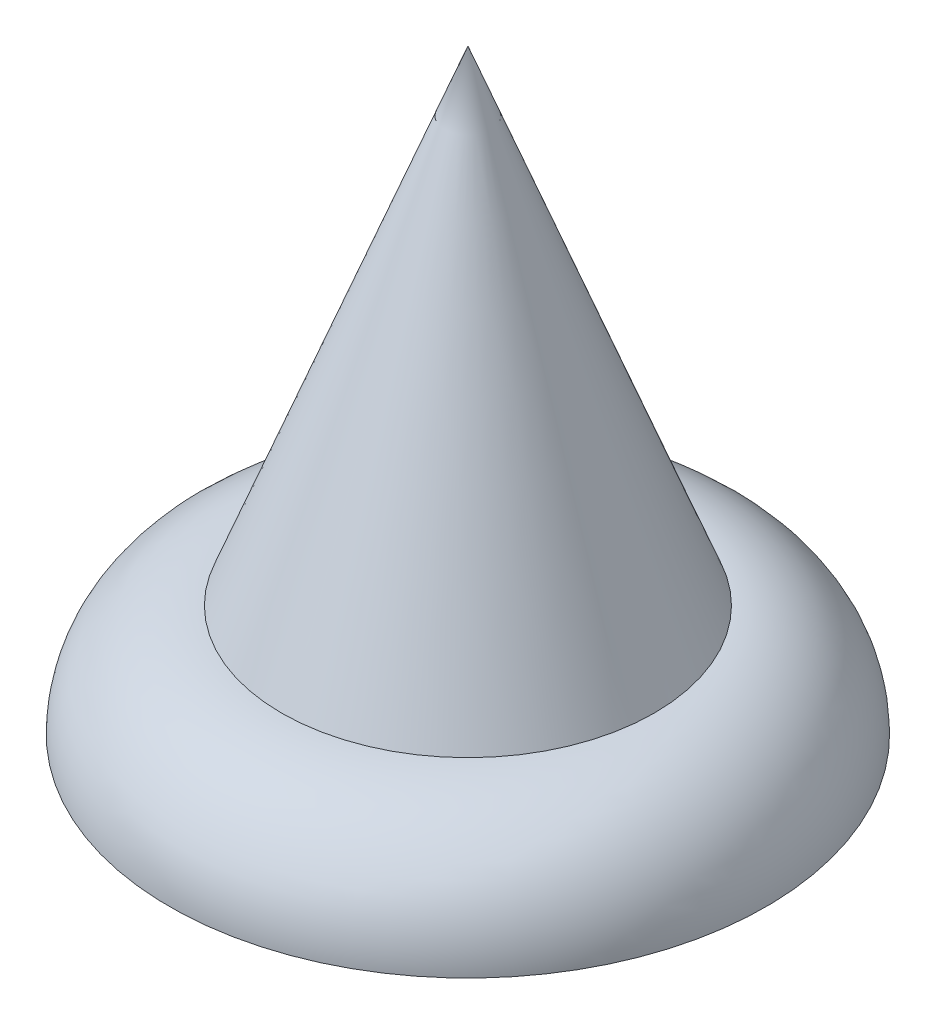
SolidWorks part; units mm, degrees
material "ABS"
ref_plane "正面" through (0, 0, 0) normal (0, 0, 1) x (1, 0, 0)
ref_plane "平面" through (0, 0, 0) normal (0, 1, 0) x (1, 0, 0)
ref_plane "右側面" through (0, 0, 0) normal (1, 0, 0) x (0, 0, -1)
sketch "ｽｹｯﾁ1" plane through (0, 0, 0) normal (0, 0, 1) x (1, 0, 0)
  line L0 (0, 0) -> (0, 7.5)
  line L1 (0, 7.5) -> (-12.5, 7.5)
  line L2 (0, 0) -> (-20, 0)
  arc A0 (-12.5, 7.5) -> (-20, 0) centre (-12.5, 0) ccw
  point P7 (-20, 0)
  dimension "D1" = 20
  dimension "D2" = 7.5
revolve "回転1" add sketch "ｽｹｯﾁ1" angle 360 about L0
sketch "ｽｹｯﾁ3" plane through (0, 0, 0) normal (0, 0, 1) x (1, 0, 0)
  line L0 (0, 7.5) -> (0, 40)
  line L1 (0, 40) -> (-12.5, 7.5)
  line L2 (-12.5, 7.5) -> (0, 7.5)
  point P3 (0, 0)
  dimension "D1" = 32.5
revolve "回転2" add sketch "ｽｹｯﾁ3" angle 360 about L0
sketch "ｽｹｯﾁ4" plane through (0, 0, 0) normal (0, -1, 0) x (1, 0, 0)
  circle A0 centre (0, 0) radius 1.1
  dimension "D1" = 2.2
extrude "ｶｯﾄ - 押し出し1" cut sketch "ｽｹｯﾁ4" against normal through all
sketch "ｽｹｯﾁ5" plane through (0, 7.5, 0) normal (0, -1, 0) x (1, 0, 0)
  circle A0 centre (0, 0) radius 0.85
  dimension "D1" = 1.7
extrude "ｶｯﾄ - 押し出し2" cut sketch "ｽｹｯﾁ5" against normal blind 10
